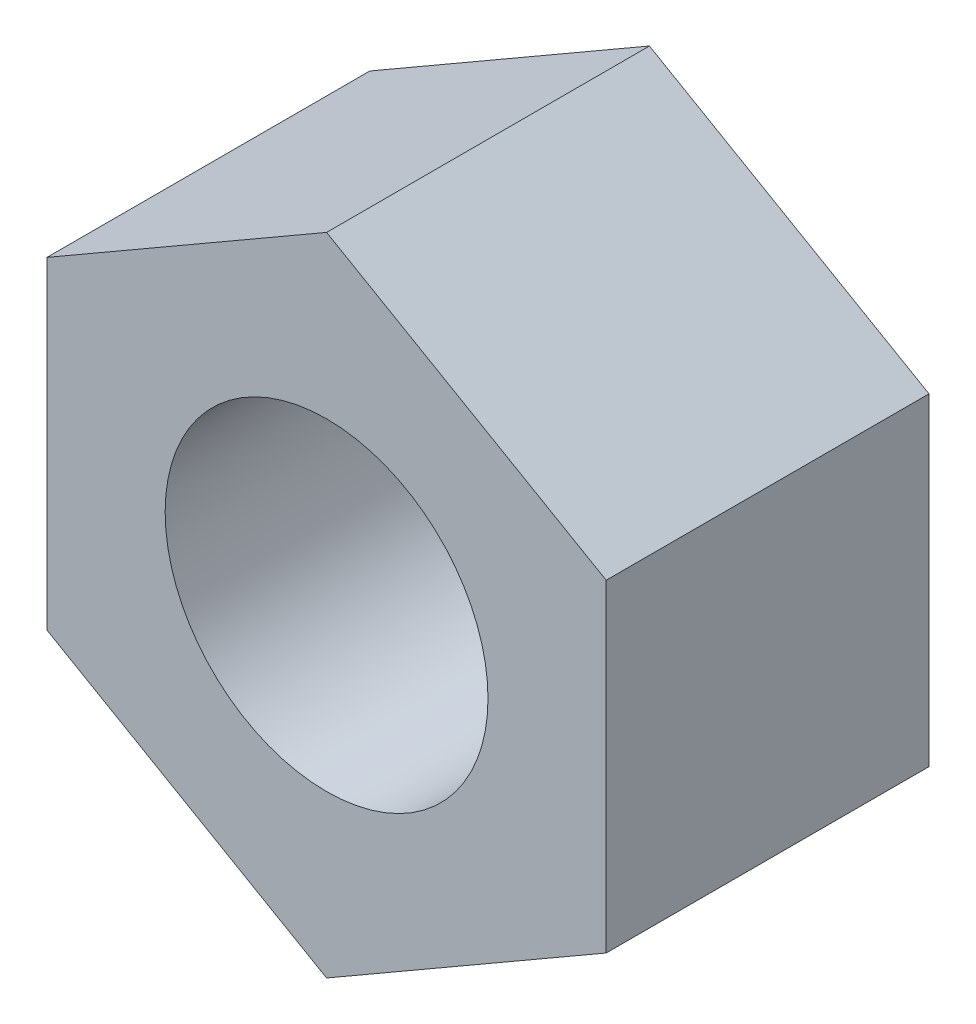
SolidWorks part; units mm, degrees
ref_plane "Front Plane" through (0, 0, 0) normal (0, 0, 1) x (1, 0, 0)
ref_plane "Top Plane" through (0, 0, 0) normal (0, 1, 0) x (1, 0, 0)
ref_plane "Right Plane" through (0, 0, 0) normal (1, 0, 0) x (0, 0, -1)
sketch "Sketch1" plane through (0, 0, 0) normal (0, 0, 1) x (1, 0, 0)
  line L1 (0, 2) -> (-1.7321, 1)
  line L2 (-1.7321, 1) -> (-1.7321, -1)
  line L3 (-1.7321, -1) -> (0, -2)
  line L4 (0, -2) -> (1.7321, -1)
  line L5 (1.7321, -1) -> (1.7321, 1)
  line L6 (1.7321, 1) -> (0, 2)
  circle A0 centre (0, 0) radius 1.7321 construction
  dimension "D1" = 2
extrude "Boss-Extrude1" add sketch "Sketch1" along normal blind 2
sketch "Sketch2" plane through (0, 0, 0) normal (0, 0, -1) x (-1, 0, 0)
  circle A0 centre (0, 0) radius 1
  dimension "D1" = 2
extrude "Cut-Extrude1" cut sketch "Sketch2" against normal blind 3 contours A0
